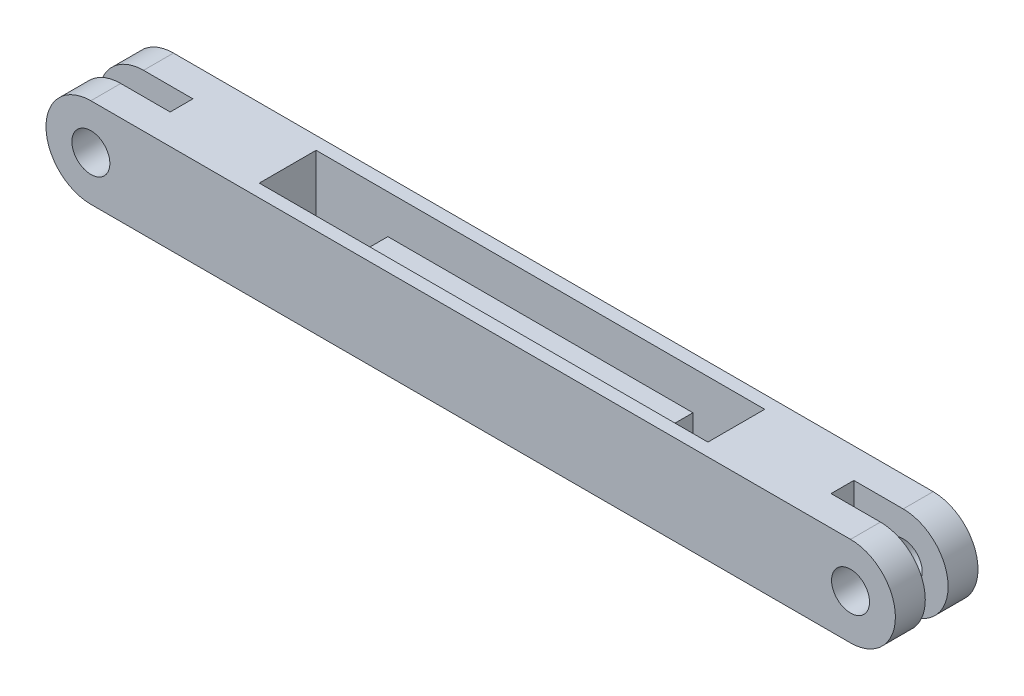
SolidWorks part; units mm, degrees
ref_plane "Front" through (0, 0, 0) normal (0, 0, 1) x (1, 0, 0)
ref_plane "Top" through (0, 0, 0) normal (0, 1, 0) x (1, 0, 0)
ref_plane "Right" through (0, 0, 0) normal (1, 0, 0) x (0, 0, -1)
sketch "Sketch1" plane through (0, 0, 0) normal (0, 0, 1) x (1, 0, 0)
  line L0 (-47.2174, 0.4239) -> (79.7826, 0.4239) construction
  line L1 (-47.2174, 7.9239) -> (79.7826, 7.9239)
  line L2 (-47.2174, -7.0761) -> (79.7826, -7.0761)
  arc A0 (-47.2174, 7.9239) -> (-47.2174, -7.0761) centre (-47.2174, 0.4239) ccw
  arc A1 (79.7826, -7.0761) -> (79.7826, 7.9239) centre (79.7826, 0.4239) ccw
  circle A2 centre (-47.2174, 0.4239) radius 3.175
  circle A3 centre (79.7826, 0.4239) radius 3.175
  point P2 (16.2826, 0.4239)
  dimension "D1" = 7.5
  dimension "D3" = 6.35
  dimension "D4" = 6.35
  dimension "D2" = 127
extrude "Boss-Extrude1" add sketch "Sketch1" along normal blind 5
sketch "Sketch2" plane through (0, 0, 5) normal (0, 0, 1) x (1, 0, 0)
  line L2 (-38.9624, -7.0761) -> (-38.9624, 7.9239)
  line L4 (79.7826, 7.9239) -> (-47.2174, 7.9239) construction
  line L9 (71.5276, -7.0761) -> (71.5276, 7.9239)
  line L10 (-38.9624, 7.9239) -> (71.5276, 7.9239)
  line L11 (-38.9624, -7.0761) -> (71.5276, -7.0761)
  point P13 (-38.9624, 0.4239)
  point P16 (16.9972, 0.4239)
  point P24 (71.5276, 0.4239)
extrude "Boss-Extrude2" add sketch "Sketch2" along normal blind 3.81
sketch "Sketch5" plane through (0, 0, 8.81) normal (0, 0, 1) x (1, 0, 0)
  line L0 (-47.2174, 0.4239) -> (79.7826, 0.4239) construction
  line L1 (-47.2174, 7.9239) -> (79.7826, 7.9239)
  line L2 (-47.2174, -7.0761) -> (79.7826, -7.0761)
  arc A0 (-47.2174, 7.9239) -> (-47.2174, -7.0761) centre (-47.2174, 0.4239) ccw
  arc A1 (79.7826, -7.0761) -> (79.7826, 7.9239) centre (79.7826, 0.4239) ccw
  circle A2 centre (-47.2174, 0.4239) radius 3.175
  circle A3 centre (79.7826, 0.4239) radius 3.175
  point P4 (16.2826, 0.4239)
  dimension "D1" = 7.5
  dimension "D2" = 6.35
  dimension "D3" = 6.35
extrude "Boss-Extrude3" add sketch "Sketch5" along normal blind 5
sketch "Sketch6" plane through (0, 7.9239, 0) normal (0, 1, 0) x (1, 0, 0)
  line L0 (16.2826, 0) -> (16.2826, -13.81)
  line L1 (79.7826, 0) -> (-47.2174, 0) construction
  line L2 (79.7826, -13.81) -> (-47.2174, -13.81) construction
  line L3 (-38.9624, -6.905) -> (71.5276, -6.905)
  line L4 (-38.9624, -8.81) -> (-38.9624, -5) construction
  line L5 (71.5276, -8.81) -> (71.5276, -5) construction
  line L7 (-21.2174, -11.655) -> (53.7826, -11.655)
  line L8 (-21.2174, -11.655) -> (-21.2174, -2.155)
  line L9 (-21.2174, -2.155) -> (53.7826, -2.155)
  line L10 (53.7826, -11.655) -> (53.7826, -2.155)
  line L11 (-21.2174, -11.655) -> (53.7826, -2.155) construction
  line L12 (-21.2174, -2.155) -> (53.7826, -11.655) construction
  point P12 (16.2826, -6.905)
  point P17 (0, 0)
extrude "Cut-Extrude1" cut sketch "Sketch6" against normal blind 6.5 contours L7 L10 L9 L8
sketch "Sketch7" plane through (0, 1.4239, 0) normal (0, 1, 0) x (1, 0, 0)
  line L0 (-21.2174, -11.655) -> (53.7826, -11.655) construction
  line L1 (-21.2174, -2.155) -> (-9.2174, -2.155)
  line L2 (-21.2174, -2.155) -> (-21.2174, -11.655)
  line L3 (-21.2174, -11.655) -> (-9.2174, -11.655)
  line L4 (-9.2174, -2.155) -> (-9.2174, -11.655)
  line L6 (53.7826, -2.155) -> (41.7826, -2.155)
  line L7 (53.7826, -2.155) -> (53.7826, -11.655)
  line L8 (53.7826, -11.655) -> (41.7826, -11.655)
  line L9 (41.7826, -2.155) -> (41.7826, -11.655)
extrude "Cut-Extrude2" cut sketch "Sketch7" against normal blind 9.294
